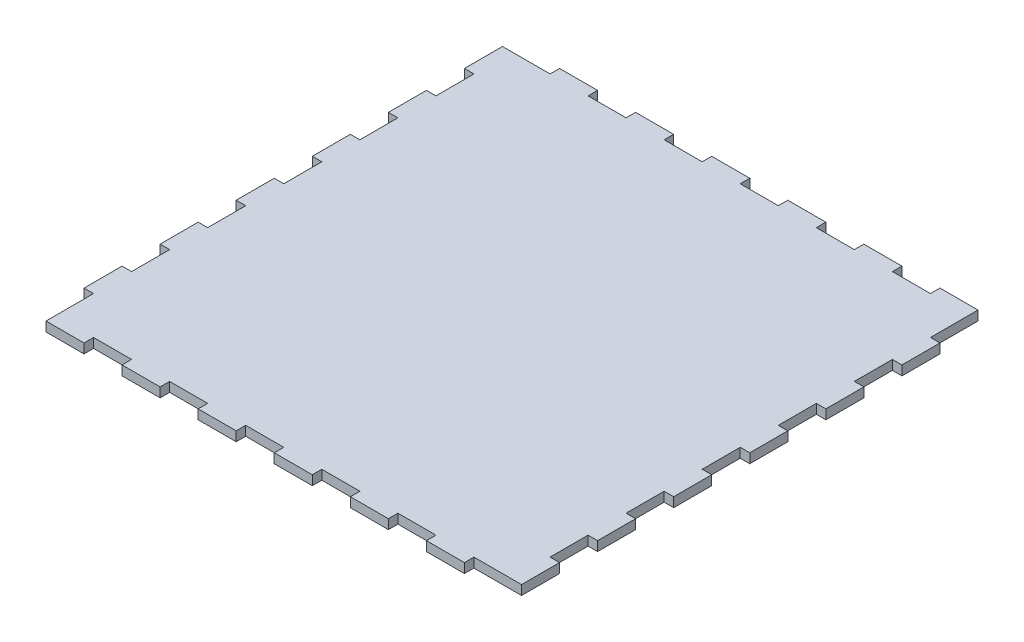
SolidWorks part; units mm, degrees
ref_plane "Front Plane" through (0, 0, 0) normal (0, 0, 1) x (1, 0, 0)
ref_plane "Top Plane" through (0, 0, 0) normal (0, 1, 0) x (1, 0, 0)
ref_plane "Right Plane" through (0, 0, 0) normal (1, 0, 0) x (0, 0, -1)
sketch "Sketch1" plane through (0, 0, 0) normal (0, 1, 0) x (1, 0, 0)
  line L0 (-65.2925, -101.6) -> (-39.8925, -101.6)
  line L1 (-97.0425, 152.4) -> (-97.0425, 127)
  line L2 (-97.0425, 203.2) -> (-97.0425, 177.8)
  line L3 (-90.6925, -107.95) -> (-65.2925, -107.95)
  line L4 (188.7075, 209.55) -> (214.1075, 209.55)
  line L5 (-90.6925, 177.8) -> (-90.6925, 152.4)
  line L6 (-97.0425, 203.2) -> (-65.2925, 203.2)
  line L7 (214.1075, 209.55) -> (214.1075, 177.8)
  line L8 (-65.2925, 209.55) -> (-65.2925, 203.2)
  line L9 (-39.8925, 209.55) -> (-39.8925, 203.2)
  line L10 (-14.4925, 209.55) -> (-14.4925, 203.2)
  line L11 (36.3075, 209.55) -> (36.3075, 203.2)
  line L12 (61.7075, 209.55) -> (61.7075, 203.2)
  line L13 (87.1075, 209.55) -> (87.1075, 203.2)
  line L14 (112.5075, 209.55) -> (112.5075, 203.2)
  line L15 (10.9075, 209.55) -> (10.9075, 203.2)
  line L16 (137.9075, 209.55) -> (137.9075, 203.2)
  line L17 (163.3075, 209.55) -> (163.3075, 203.2)
  line L18 (188.7075, 209.55) -> (188.7075, 203.2)
  line L19 (-97.0425, -76.2) -> (-90.6925, -76.2)
  line L20 (-97.0425, -50.8) -> (-90.6925, -50.8)
  line L21 (-97.0425, -25.4) -> (-90.6925, -25.4)
  line L22 (-97.0425, 0) -> (-90.6925, 0)
  line L23 (-97.0425, 25.4) -> (-90.6925, 25.4)
  line L24 (-97.0425, 50.8) -> (-90.6925, 50.8)
  line L25 (-97.0425, 76.2) -> (-90.6925, 76.2)
  line L26 (-97.0425, 101.6) -> (-90.6925, 101.6)
  line L27 (-97.0425, 127) -> (-90.6925, 127)
  line L28 (-97.0425, 152.4) -> (-90.6925, 152.4)
  line L29 (-97.0425, 177.8) -> (-90.6925, 177.8)
  line L30 (-39.8925, -107.95) -> (-14.4925, -107.95)
  line L31 (10.9075, -107.95) -> (36.3075, -107.95)
  line L32 (61.7075, -107.95) -> (87.1075, -107.95)
  line L33 (112.5075, -107.95) -> (137.9075, -107.95)
  line L34 (163.3075, -107.95) -> (188.7075, -107.95)
  line L35 (220.4575, -76.2) -> (220.4575, -101.6)
  line L36 (220.4575, -25.4) -> (220.4575, -50.8)
  line L37 (220.4575, 25.4) -> (220.4575, 0)
  line L38 (220.4575, 76.2) -> (220.4575, 50.8)
  line L39 (220.4575, 127) -> (220.4575, 101.6)
  line L40 (220.4575, 177.8) -> (220.4575, 152.4)
  line L41 (137.9075, 209.55) -> (163.3075, 209.55)
  line L42 (87.1075, 209.55) -> (112.5075, 209.55)
  line L43 (36.3075, 209.55) -> (61.7075, 209.55)
  line L44 (-14.4925, 209.55) -> (10.9075, 209.55)
  line L45 (-65.2925, 209.55) -> (-39.8925, 209.55)
  line L46 (-97.0425, 101.6) -> (-97.0425, 76.2)
  line L47 (-97.0425, 50.8) -> (-97.0425, 25.4)
  line L48 (-97.0425, 0) -> (-97.0425, -25.4)
  line L49 (-97.0425, -50.8) -> (-97.0425, -76.2)
  line L50 (-39.8925, 203.2) -> (-14.4925, 203.2)
  line L51 (10.9075, 203.2) -> (36.3075, 203.2)
  line L52 (61.7075, 203.2) -> (87.1075, 203.2)
  line L53 (112.5075, 203.2) -> (137.9075, 203.2)
  line L54 (163.3075, 203.2) -> (188.7075, 203.2)
  line L66 (-90.6925, -76.2) -> (-90.6925, -107.95)
  line L67 (-90.6925, 127) -> (-90.6925, 101.6)
  line L68 (-90.6925, 76.2) -> (-90.6925, 50.8)
  line L69 (-90.6925, 25.4) -> (-90.6925, 0)
  line L70 (-90.6925, -25.4) -> (-90.6925, -50.8)
  line L71 (-14.4925, -101.6) -> (10.9075, -101.6)
  line L72 (36.3075, -101.6) -> (61.7075, -101.6)
  line L73 (87.1075, -101.6) -> (112.5075, -101.6)
  line L74 (137.9075, -101.6) -> (163.3075, -101.6)
  line L75 (188.7075, -101.6) -> (220.4575, -101.6)
  line L76 (214.1075, -50.8) -> (214.1075, -76.2)
  line L77 (214.1075, 0) -> (214.1075, -25.4)
  line L78 (214.1075, 50.8) -> (214.1075, 25.4)
  line L79 (214.1075, 76.2) -> (220.4575, 76.2)
  line L80 (214.1075, 101.6) -> (214.1075, 76.2)
  line L81 (214.1075, 152.4) -> (214.1075, 127)
  line L82 (214.1075, 177.8) -> (220.4575, 177.8)
  line L83 (214.1075, 152.4) -> (220.4575, 152.4)
  line L84 (214.1075, 127) -> (220.4575, 127)
  line L85 (214.1075, 101.6) -> (220.4575, 101.6)
  line L86 (214.1075, 50.8) -> (220.4575, 50.8)
  line L87 (214.1075, 25.4) -> (220.4575, 25.4)
  line L88 (214.1075, 0) -> (220.4575, 0)
  line L89 (214.1075, -25.4) -> (220.4575, -25.4)
  line L90 (214.1075, -50.8) -> (220.4575, -50.8)
  line L91 (214.1075, -76.2) -> (220.4575, -76.2)
  line L92 (188.7075, -101.6) -> (188.7075, -107.95)
  line L93 (163.3075, -101.6) -> (163.3075, -107.95)
  line L94 (137.9075, -101.6) -> (137.9075, -107.95)
  line L95 (112.5075, -101.6) -> (112.5075, -107.95)
  line L96 (87.1075, -101.6) -> (87.1075, -107.95)
  line L97 (61.7075, -101.6) -> (61.7075, -107.95)
  line L98 (36.3075, -101.6) -> (36.3075, -107.95)
  line L99 (10.9075, -101.6) -> (10.9075, -107.95)
  line L100 (-14.4925, -101.6) -> (-14.4925, -107.95)
  line L101 (-39.8925, -101.6) -> (-39.8925, -107.95)
  line L102 (-65.2925, -101.6) -> (-65.2925, -107.95)
  dimension "D3" = 6.35
  dimension "D4" = 6.35
  dimension "D7" = 25.4
  dimension "D8" = 50.8
  dimension "D9" = 76.2
  dimension "D10" = 101.6
  dimension "D11" = 127
  dimension "D12" = 152.4
  dimension "D13" = 177.8
  dimension "D14" = 203.2
  dimension "D15" = 228.6
  dimension "D16" = 254
  dimension "D17" = 279.4
  dimension "D18" = 25.4
  dimension "D19" = 50.8
  dimension "D20" = 76.2
  dimension "D21" = 101.6
  dimension "D22" = 127
  dimension "D23" = 152.4
  dimension "D24" = 177.8
  dimension "D25" = 203.2
  dimension "D26" = 228.6
  dimension "D27" = 254
  dimension "D28" = 279.4
  dimension "D29" = 304.8
extrude "Boss-Extrude1" add sketch "Sketch1" along normal blind 6.35
